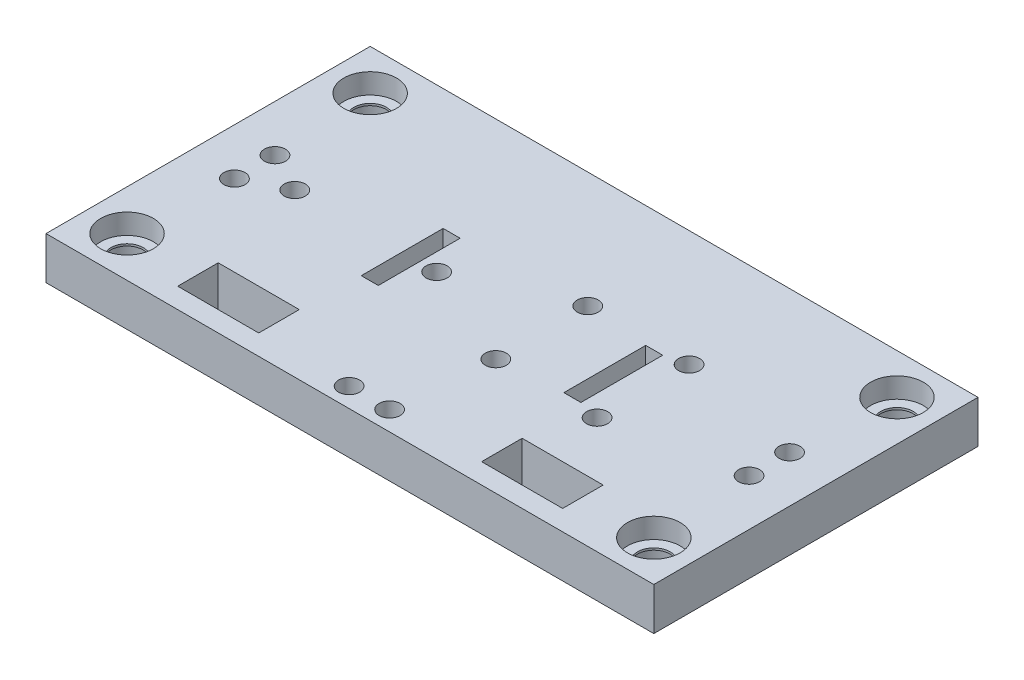
SolidWorks part; units mm, degrees
ref_plane "Front Plane" through (0, 0, 0) normal (0, 0, 1) x (1, 0, 0)
ref_plane "Top Plane" through (0, 0, 0) normal (0, 1, 0) x (1, 0, 0)
ref_plane "Right Plane" through (0, 0, 0) normal (1, 0, 0) x (0, 0, -1)
sketch "Sketch1" plane through (0, 0, 0) normal (0, 1, 0) x (1, 0, 0)
  line L1 (0, 0) -> (150, 0)
  line L2 (0, 0) -> (0, 80)
  line L3 (0, 80) -> (150, 80)
  line L4 (150, 0) -> (150, 80)
  dimension "D1" = 80
  dimension "D2" = 150
extrude "Boss-Extrude1" add sketch "Sketch1" along normal blind 10.5
sketch "Sketch10" plane through (0, 10.5, 0) normal (0, 1, 0) x (1, 0, 0)
  line L0 (75, 80) -> (75, 0) construction
  line L1 (0, 40) -> (150, 40) construction
  line L4 (0, 80) -> (0, 0)
  line L5 (0, 80) -> (0, 0) construction
  line L6 (0, 0) -> (150, 0)
  line L7 (0, 0) -> (150, 0) construction
  line L8 (150, 0) -> (150, 80)
  line L9 (150, 0) -> (150, 80) construction
  line L10 (150, 80) -> (0, 80)
  line L11 (150, 80) -> (0, 80) construction
  circle A0 centre (10, 10) radius 6.5
  circle A1 centre (140, 10) radius 6.5
  circle A3 centre (10, 70) radius 6.5
  circle A4 centre (140, 70) radius 6.5
  circle A5 centre (10, 10) radius 7.5
  circle A6 centre (10, 70) radius 7.5
  circle A7 centre (140, 70) radius 7.5
  circle A8 centre (140, 10) radius 7.5
  dimension "D4" = 13
  dimension "D2" = 10
  dimension "D3" = 10
  dimension "D1" = 0
  dimension "D5" = 1
extrude "Cut-Extrude8" cut sketch "Sketch10" against normal blind 5 contours A0 | A3 | A4 | A1 | L5 L7 L9 L11
ref_plane "MirrorPlane1" through (0, 5.25, 0) normal (0, 1, 0) x (1, 0, 0)
ref_plane "MirrorPlane2" through (0, 0, -40) normal (0, 0, 1) x (1, 0, 0)
ref_plane "MirrorPlane3" through (75, 0, 0) normal (-1, 0, 0) x (0, 0, 1)
mirror "Mirror1" about plane through (0, 5.25, 0) normal (0, 1, 0) of "Cut-Extrude8"
sketch "Sketch3" plane through (0, 10.5, 0) normal (0, 1, 0) x (1, 0, 0)
  line L0 (75, 80) -> (75, 0) construction
  line L5 (150, 80) -> (0, 80) construction
  line L6 (75, 5.775) -> (75, -5.775) construction
  line L7 (0, 0) -> (150, 0) construction
  line L8 (27.5, 15) -> (47.5, 15)
  line L9 (27.5, 15) -> (27.5, 5)
  line L10 (27.5, 5) -> (47.5, 5)
  line L11 (47.5, 15) -> (47.5, 5)
  line L12 (27.5, 15) -> (47.5, 5) construction
  line L13 (27.5, 5) -> (47.5, 15) construction
  line L15 (75, 80) -> (0, 0) construction
  line L16 (122.5, 5) -> (102.5, 5)
  line L17 (102.5, 15) -> (102.5, 5)
  line L18 (122.5, 15) -> (102.5, 15)
  line L19 (122.5, 15) -> (122.5, 5)
  point P0 (37.5, 10)
  point P16 (37.5, 40)
  dimension "D1" = 10
  dimension "D2" = 10
  dimension "D3" = 20
extrude "WireHoles" cut sketch "Sketch3" against normal up to next
sketch "Sketch6" plane through (0, 10.5, 0) normal (0, 1, 0) x (1, 0, 0)
  line L0 (75, 80) -> (75, 0) construction
  line L1 (150, 80) -> (0, 80) construction
  line L2 (0, 0) -> (150, 0) construction
  line L3 (38.9, 40) -> (21.4, 40) construction
  line L4 (73, 28.4) -> (4.8, 28.4) construction
  line L5 (73, 28.4) -> (73, 51.6) construction
  line L6 (73, 51.6) -> (4.8, 51.6) construction
  line L7 (4.8, 28.4) -> (4.8, 51.6) construction
  line L8 (73, 28.4) -> (4.8, 51.6) construction
  line L9 (73, 51.6) -> (4.8, 28.4) construction
  line L10 (38.9, 51.6) -> (38.9, 28.4) construction
  circle A0 centre (21.4, 40) radius 2.6
  circle A1 centre (56.4, 40) radius 2.6
  point P8 (38.9, 40)
  point P18 (75, 40)
  dimension "D5" = 5.2
  dimension "D1" = 68.2
  dimension "D2" = 23.2
  dimension "D3" = 2
  dimension "D4" = 17.5
extrude "4AACut" cut sketch "Sketch6" against normal blind 5.2
sketch "Sketch7" plane through (0, 10.5, 0) normal (0, 1, 0) x (1, 0, 0)
  line L0 (94.85, 51.35) -> (82.35, 51.35) construction
  line L1 (77, 42) -> (112.7, 42) construction
  line L2 (77, 42) -> (77, 60.7) construction
  line L3 (77, 60.7) -> (112.7, 60.7) construction
  line L4 (112.7, 42) -> (112.7, 60.7) construction
  line L5 (77, 42) -> (112.7, 60.7) construction
  line L6 (77, 60.7) -> (112.7, 42) construction
  line L7 (94.85, 60.7) -> (94.85, 42) construction
  line L8 (75, 80) -> (75, 0) construction
  line L9 (150, 80) -> (0, 80) construction
  line L10 (0, 0) -> (150, 0) construction
  line L11 (0, 40) -> (150, 40) construction
  line L12 (0, 80) -> (0, 0) construction
  line L13 (150, 0) -> (150, 80) construction
  circle A0 centre (82.35, 51.35) radius 2.6
  circle A1 centre (56.4, 40) radius 2.6 construction
  circle A2 centre (107.35, 51.35) radius 2.6
  circle A3 centre (82.35, 28.65) radius 2.6
  circle A4 centre (107.35, 28.65) radius 2.6
  point P0 (94.85, 51.35)
  dimension "D1" = 35.7
  dimension "D2" = 18.7
  dimension "D3" = 2
  dimension "D4" = 2
  dimension "D5" = 12.5
extrude "2AACut" cut sketch "Sketch7" against normal blind 5.2
sketch "Sketch5" plane through (0, 10.5, 0) normal (0, 1, 0) x (1, 0, 0)
  line L0 (75, 80) -> (75, 0) construction
  line L5 (150, 80) -> (0, 80) construction
  line L6 (0, 0) -> (150, 0) construction
  line L7 (50, 40) -> (75, 40) construction
  line L12 (47.9, 29.9) -> (52.1, 29.9)
  line L13 (47.9, 29.9) -> (47.9, 50.1)
  line L14 (47.9, 50.1) -> (52.1, 50.1)
  line L15 (52.1, 29.9) -> (52.1, 50.1)
  line L16 (47.9, 29.9) -> (52.1, 50.1) construction
  line L17 (47.9, 50.1) -> (52.1, 29.9) construction
  line L18 (102.1, 50.1) -> (97.9, 50.1)
  line L19 (97.9, 29.9) -> (97.9, 50.1)
  line L20 (102.1, 29.9) -> (97.9, 29.9)
  line L21 (102.1, 29.9) -> (102.1, 50.1)
  point P0 (50, 40)
  dimension "D1" = 25
  dimension "D2" = 4.2
  dimension "D3" = 20.2
extrude "ArduinoMegaCut" cut sketch "Sketch5" against normal blind 5.2
sketch "Sketch8" plane through (0, 10.5, 0) normal (0, 1, 0) x (1, 0, 0)
  line L0 (150, 80) -> (0, 80) construction
  line L5 (62.4, -2.5) -> (87.6, -2.5) construction
  line L6 (62.4, -2.5) -> (62.4, 12.1) construction
  line L7 (62.4, 12.1) -> (87.6, 12.1) construction
  line L8 (87.6, -2.5) -> (87.6, 12.1) construction
  line L9 (75, 80) -> (75, 0) construction
  line L10 (0, 0) -> (150, 0) construction
  line L11 (87.6, 4.8) -> (62.4, 4.8) construction
  circle A1 centre (70, 4.8) radius 2.6
  circle A2 centre (56.4, 40) radius 2.6 construction
  circle A3 centre (80, 4.8) radius 2.6
  point P10 (75, 12.1)
  dimension "D1" = 14.6
  dimension "D2" = 25.2
  dimension "D3" = 2.5
  dimension "D4" = 5
extrude "MPUCut" cut sketch "Sketch8" against normal blind 5.2
sketch "Sketch9" plane through (0, 10.5, 0) normal (0, 1, 0) x (1, 0, 0)
  line L0 (150, 0) -> (150, 80) construction
  line L1 (127, 51.225) -> (150, 51.225)
  line L2 (127, 51.225) -> (127, 28.775)
  line L3 (127, 28.775) -> (150, 28.775)
  line L4 (150, 51.225) -> (150, 28.775)
  line L5 (127, 51.225) -> (150, 28.775) construction
  line L6 (127, 28.775) -> (150, 51.225) construction
  line L9 (0, 40) -> (150, 40) construction
  line L10 (0, 80) -> (0, 0) construction
  line L11 (75, 80) -> (75, 0) construction
  line L12 (150, 80) -> (0, 80) construction
  line L13 (0, 0) -> (150, 0) construction
  circle A0 centre (138.5, 45) radius 2.6
  circle A1 centre (107.35, 51.35) radius 2.6 construction
  circle A2 centre (138.5, 35) radius 2.6
  circle A3 centre (11.5, 35) radius 2.6
  circle A4 centre (11.5, 45) radius 2.6
  point P0 (138.5, 40)
  dimension "D1" = 22.45
  dimension "D2" = 23
  dimension "D3" = 5
extrude "Cut-Extrude7" cut sketch "Sketch9" against normal up to next contours A0 | A2 | A4 | A3
sketch "Sketch11" plane through (0, 5.5, 0) normal (0, 1, 0) x (1, 0, 0)
  line L0 (0, 40) -> (150, 40) construction
  line L1 (0, 80) -> (0, 0) construction
  line L2 (150, 0) -> (150, 80) construction
  line L3 (75, 80) -> (75, 0) construction
  line L4 (150, 80) -> (0, 80) construction
  line L5 (0, 0) -> (150, 0) construction
  circle A0 centre (10, 10) radius 4
  circle A1 centre (10, 70) radius 4
  circle A2 centre (140, 70) radius 4
  circle A3 centre (140, 10) radius 4
  dimension "D1" = 8
extrude "Cut-Extrude9" cut sketch "Sketch11" against normal up to surface (0.5 mm away) up to face at (10, 5, -63.5)
equation "\"Depth\"= 5.20"
